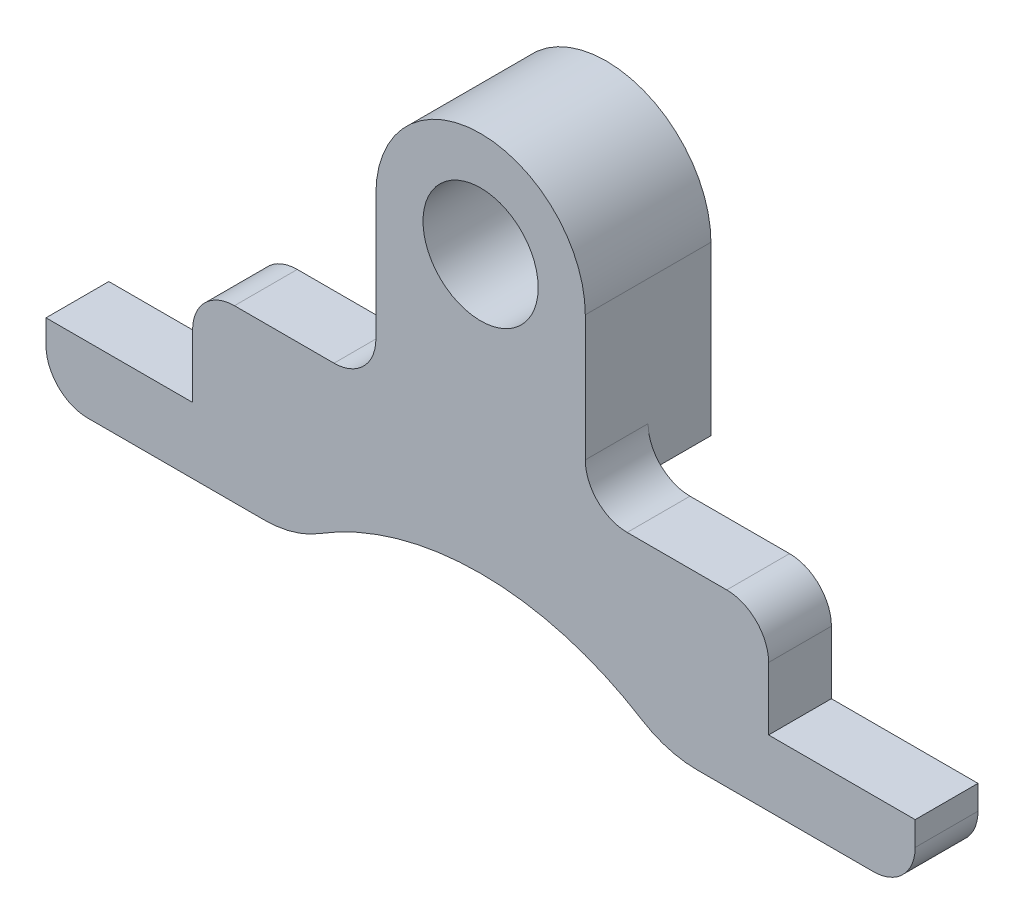
SolidWorks part; units mm, degrees
ref_plane "Front Plane" through (0, 0, 0) normal (0, 0, 1) x (1, 0, 0)
ref_plane "Top Plane" through (0, 0, 0) normal (0, 1, 0) x (1, 0, 0)
ref_plane "Right Plane" through (0, 0, 0) normal (1, 0, 0) x (0, 0, -1)
sketch "Sketch2" plane through (0, 0, 0) normal (0, 0, 1) x (1, 0, 0)
  line L15 (-5, 27.75) -> (-5, 19.75)
  line L16 (5, 27.75) -> (5, 19.75)
  line L18 (-5, 19.75) -> (5, 19.75)
  circle A0 centre (0, 27.75) radius 2.75 construction
  circle A1 centre (0, 27.75) radius 2.75
  circle A2 centre (0, 27.75) radius 5
  arc A3 (14.1624, 3.3636) -> (-14.1624, 3.3636) centre (0, 0) ccw construction
  arc A4 (14.1624, 3.3636) -> (8.7435, 11.6378) centre (0, 0) ccw
  arc A5 (-8.7435, 11.6378) -> (-14.1624, 3.3636) centre (0, 0) ccw
  circle M3 centre (0, 27.75) radius 2.75
  dimension "D1" = 10
extrude "Boss-Extrude1" add sketch "Sketch2" along normal blind 6 contours A2 M3 | A2 L15 L18 L16
sketch "Sketch3" plane through (0, 0, 3) normal (0, 0, 1) x (1, 0, 0)
  line L0 (-5, 19.75) -> (-13.7532, 19.75)
  line L1 (-20.7532, 19.75) -> (-13.7532, 19.75)
  line L2 (-20.7532, 19.75) -> (-20.7532, 14.75)
  line L3 (-20.7532, 14.75) -> (-13.7532, 14.75)
  line L4 (-13.7532, 19.75) -> (-13.7532, 14.75)
  line L5 (20.7532, 19.75) -> (13.7532, 19.75)
  line L6 (20.7532, 19.75) -> (20.7532, 14.75)
  line L7 (20.7532, 14.75) -> (13.7532, 14.75)
  line L8 (13.7532, 19.75) -> (13.7532, 14.75)
  line L9 (5, 19.75) -> (13.7532, 19.75)
  line L10 (20.7532, 14.75) -> (20.7532, 11.5988)
  line L11 (20.7532, 0) -> (20.7532, 19.75) construction
  line L12 (20.7532, 11.5988) -> (-14.9005, 11.5988)
  line L13 (-20.7532, 14.75) -> (-20.7532, 11.5988)
  line L14 (-20.7532, 19.75) -> (-20.7532, 0) construction
  line L15 (-20.7532, 11.5988) -> (-14.9005, 11.5988)
  line L16 (20.7532, 11.5988) -> (20.7532, 14.75)
  line L17 (-5, 19.75) -> (5, 19.75) construction
  line L18 (-5, 19.75) -> (5, 19.75)
  line L19 (-13.7532, 19.75) -> (13.7532, 19.75)
  line M7 (20.7532, 14.75) -> (13.7532, 14.75)
  line M8 (13.7532, 14.75) -> (13.7532, 19.75)
  line M9 (13.7532, 19.75) -> (-13.7532, 19.75)
  line M10 (-13.7532, 19.75) -> (-13.7532, 14.75)
  line M11 (-13.7532, 14.75) -> (-20.7532, 14.75)
  arc M15 (-14.1624, 3.3636) -> (14.1624, 3.3636) centre (0, 0) cw
extrude "Boss-Extrude2" add sketch "Sketch3" along normal blind 3 contours L13 L15 L12 L10 M15 M7 M8 M9 M10 M11
fillet "Fillet1" radius 2 6 edges at (5, 19.75, 4.5) (-5, 19.75, 4.5) (-20.7532, 11.5988, 4.5) (20.7532, 11.5988, 4.5) (13.7532, 19.75, 4.5) (-13.7532, 19.75, 4.5)
fillet "Fillet2" radius 5 2 edges at (8.7952, 11.5988, 4.5) (-8.7952, 11.5988, 4.5)
